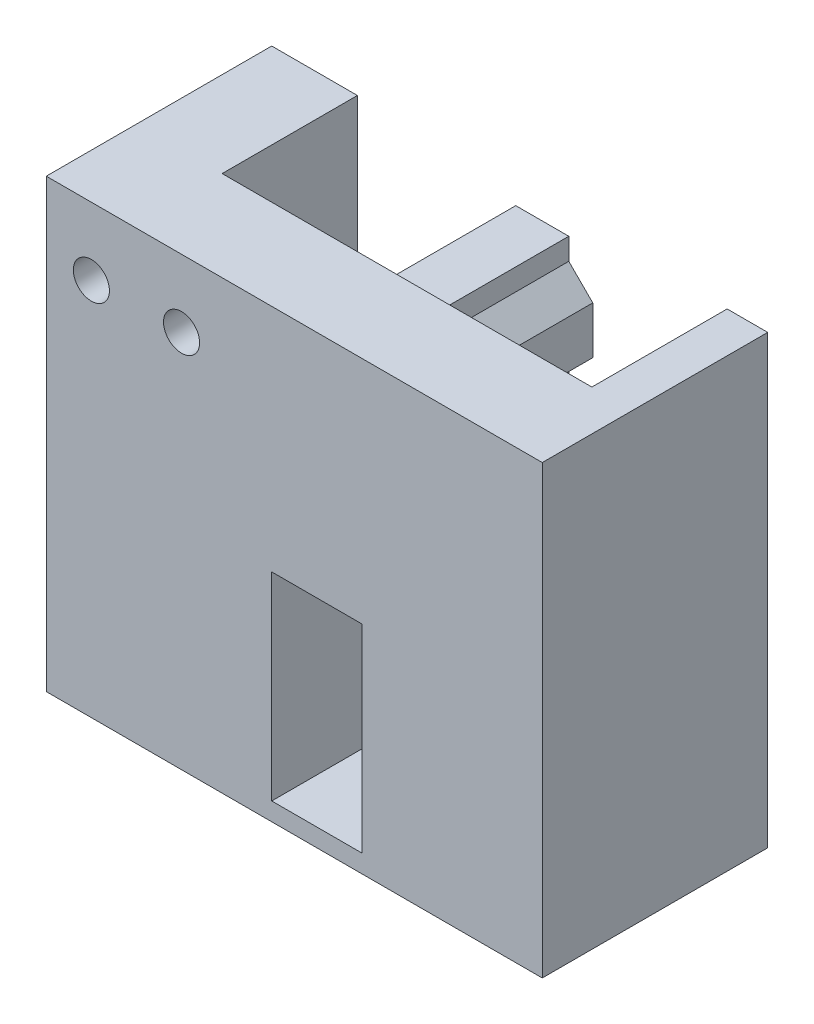
SolidWorks part; units mm, degrees
ref_plane "Front Plane" through (0, 0, 0) normal (0, 0, 1) x (1, 0, 0)
ref_plane "Top Plane" through (0, 0, 0) normal (0, 1, 0) x (1, 0, 0)
ref_plane "Right Plane" through (0, 0, 0) normal (1, 0, 0) x (0, 0, -1)
sketch "Sketch1" plane through (0, 0, 0) normal (0, 0, 1) x (1, 0, 0)
  line L0 (-16.2, -10) -> (-11.5, -10) construction
  line L1 (15, -20) -> (-40, -20)
  line L2 (15, -20) -> (15, 29.5)
  line L4 (-40, -20) -> (-40, 29.5)
  line L6 (10, 8.5) -> (10, 3.8) construction
  line L7 (-30, 28.5) -> (-30, 23.8) construction
  line L8 (-10, -10) -> (-10, 33.7547) construction
  line L9 (-8.5, -10) -> (-11.5, -10) construction
  line L10 (10.5, 10) -> (10.5, 29.5)
  line L11 (10.5, 10) -> (10.5, 3.4944)
  line L12 (10.5, 3.4944) -> (9.7, 2.6)
  line L13 (9.7, 2.6) -> (7.7, 2.6)
  line L14 (7.7, 2.6) -> (7.7, 5)
  line L17 (4.4, 2.6322) -> (4.4, -2.7831)
  line L20 (7.7, -5) -> (7.7, -2.6)
  line L21 (7.7, -2.6) -> (9.7, -2.6)
  line L22 (9.7, -2.6) -> (10.5, -3.4944)
  line L23 (10.5, -3.4944) -> (10.5, -10.5)
  line L24 (10.5, -10.5) -> (-30.5, -10.5)
  line L27 (8.5, -10) -> (3.8, -10) construction
  line L28 (8.2, -3.1) -> (9.3, -3.1) construction
  line L29 (8.2, 3.1) -> (9.3, 3.1) construction
  line L30 (3.9, 2.7565) -> (3.9, -2.7565) construction
  line L31 (8.2, 5.3) -> (8.2, 3.1) construction
  line L32 (8.2, -5.3) -> (8.2, -3.1) construction
  line L33 (10, -3.8) -> (10, -8.5) construction
  line L34 (7.7, -5) -> (6.7678, -5)
  line L35 (6.7678, -5) -> (4.4, -2.7831)
  line L37 (6.5607, -5.5) -> (8, -5.5) construction
  line L38 (4.4, 2.6322) -> (6.7678, 5)
  line L39 (3.9586, 2.8979) -> (6.5607, 5.5) construction
  line L40 (6.7678, 5) -> (7.7, 5)
  line L41 (6.5607, 5.5) -> (8, 5.5) construction
  line L43 (-26.7678, 5) -> (-27.7, 5)
  line L44 (-24.4, 2.6322) -> (-26.7678, 5)
  line L45 (-24.4, 2.6322) -> (-24.4, -2.7831)
  line L46 (-26.7678, -5) -> (-24.4, -2.7831)
  line L47 (-27.7, -5) -> (-26.7678, -5)
  line L48 (-27.7, -5) -> (-27.7, -2.6)
  line L49 (-27.7, -2.6) -> (-29.7, -2.6)
  line L50 (-29.7, -2.6) -> (-30.5, -3.4944)
  line L51 (-30.5, -3.4944) -> (-30.5, -10.5)
  line L52 (-30.5, 10) -> (-30.5, 3.4944)
  line L53 (-30.5, 3.4944) -> (-29.7, 2.6)
  line L54 (-29.7, 2.6) -> (-27.7, 2.6)
  line L55 (-27.7, 2.6) -> (-27.7, 5)
  line L56 (10.5, 29.5) -> (15, 29.5)
  line L58 (-40, 29.5) -> (-30.5, 29.5)
  line L59 (-30.5, 29.5) -> (-30.5, 10)
  dimension "D1" = 10
  dimension "D3" = 5
  dimension "D4" = 10
  dimension "D5" = 0.5
  dimension "D6" = 0.5
  dimension "D7" = 0.5
  dimension "D8" = 0.5
  dimension "D9" = 0.5
  dimension "D10" = 0.5
  dimension "D11" = 0.5
  dimension "D12" = 0.5
  dimension "D14" = 0.5
  dimension "D16" = 0.5
  dimension "D17" = 0.5
  dimension "D19" = 1.2
  dimension "D20" = 1.2
  dimension "D21" = 0.4
  dimension "D22" = 0.4
extrude "Boss-Extrude1" add sketch "Sketch1" against normal blind 15
sketch "Sketch3" plane through (0, 0, 0) normal (0, 0, 1) x (1, 0, 0)
  line L1 (15, -20) -> (-40, -20)
  line L2 (15, -20) -> (15, 29.5)
  line L3 (15, 29.5) -> (-40, 29.5)
  line L4 (-40, -20) -> (-40, 29.5)
extrude "Boss-Extrude2" add sketch "Sketch3" along normal blind 10
sketch "Sketch4" plane through (0, 0, 0) normal (0, 0, -1) x (-1, 0, 0)
  line L0 (12.9393, 25.2929) -> (15.6, 22.6322)
  line L1 (15.6, 22.6322) -> (15.6, 17.3678)
  line L2 (15.6, 17.3678) -> (12.9393, 14.7071)
  line L3 (12.9393, 14.7071) -> (12.9393, 12.3)
  line L4 (12.9393, 12.3) -> (7.0607, 12.3)
  line L5 (7.0607, 12.3) -> (7.0607, 14.7071)
  line L6 (7.0607, 14.7071) -> (4.4, 17.3678)
  line L7 (4.4, 17.3678) -> (4.4, 22.6322)
  line L8 (4.4, 22.6322) -> (7.0607, 25.2929)
  line L9 (7.0607, 25.2929) -> (7.0607, 27.7)
  line L10 (7.0607, 27.7) -> (12.9393, 27.7)
  line L11 (12.9393, 27.7) -> (12.9393, 25.2929)
  line L12 (6.5607, 11.8) -> (13.4393, 11.8) construction
  line L13 (6.5607, 28.2) -> (13.4393, 28.2) construction
  line L14 (3.9586, 22.8979) -> (6.5607, 25.5) construction
  line L15 (16.0414, 17.1021) -> (13.4393, 14.5) construction
  line L16 (13.4393, 14.5) -> (13.4393, 11.8) construction
  line L17 (6.5607, 14.5) -> (6.5607, 11.8) construction
  line L18 (3.9, 22.7565) -> (3.9, 17.2435) construction
  line L19 (16.1, 22.7565) -> (16.1, 17.2435) construction
  line L20 (16.0414, 22.8979) -> (13.4393, 25.5) construction
  line L21 (6.5607, 25.5) -> (6.5607, 28.2) construction
  line L22 (3.9586, 17.1021) -> (6.5607, 14.5) construction
  line L23 (13.4393, 25.5) -> (13.4393, 28.2) construction
  point P14 (10, 27.7)
  dimension "D1" = 0.5
  dimension "D2" = 0.5
  dimension "D3" = 0.5
  dimension "D4" = 0.5
  dimension "D5" = 0.5
  dimension "D6" = 0.5
  dimension "D7" = 0.5
  dimension "D8" = 0.5
  dimension "D9" = 0.5
  dimension "D10" = 0.5
  dimension "D11" = 0.5
  dimension "D13" = 0.5
extrude "Boss-Extrude3" add sketch "Sketch4" along normal blind 15 separate body
sketch "Sketch5" plane through (0, 0, 10) normal (0, 0, 1) x (1, 0, 0)
  line L0 (-40, 29.5) -> (-40, -20) construction
  line L1 (15, 29.5) -> (-40, 29.5) construction
  circle A0 centre (-35, 22) radius 2
  circle A1 centre (-25, 22) radius 2
  dimension "D1" = 4
  dimension "D2" = 4
  dimension "D3" = 5
  dimension "D4" = 7.5
  dimension "D5" = 15
  dimension "D6" = 7.5
extrude "Cut-Extrude1" cut sketch "Sketch5" against normal blind 7
sketch "Sketch6" plane through (0, -20, 0) normal (0, -1, 0) x (-1, 0, 0)
  line L1 (40, -10) -> (-15, -10) construction
  line L2 (40, 15) -> (40, -10) construction
  circle A0 centre (35, -1) radius 2
  circle A1 centre (25, -1) radius 2
  dimension "D1" = 4
  dimension "D2" = 9
  dimension "D3" = 5
  dimension "D4" = 4
  dimension "D5" = 9
  dimension "D6" = 10
extrude "Cut-Extrude2" cut sketch "Sketch6" against normal blind 7
sketch "Sketch7" plane through (0, 0, 10) normal (0, 0, 1) x (1, 0, 0)
  line L0 (-40, -20) -> (15, -20) construction
  line L1 (-15, 4) -> (-5, 4)
  line L2 (-15, 4) -> (-15, -18)
  line L3 (-15, -18) -> (-5, -18)
  line L4 (-5, 4) -> (-5, -18)
  point P4 (-10, -18)
  point P7 (-12.5, -20)
  dimension "D1" = 2.5
  dimension "D2" = 2
  dimension "D3" = 22
  dimension "D4" = 10
extrude "Cut-Extrude3" cut sketch "Sketch7" against normal blind 43
